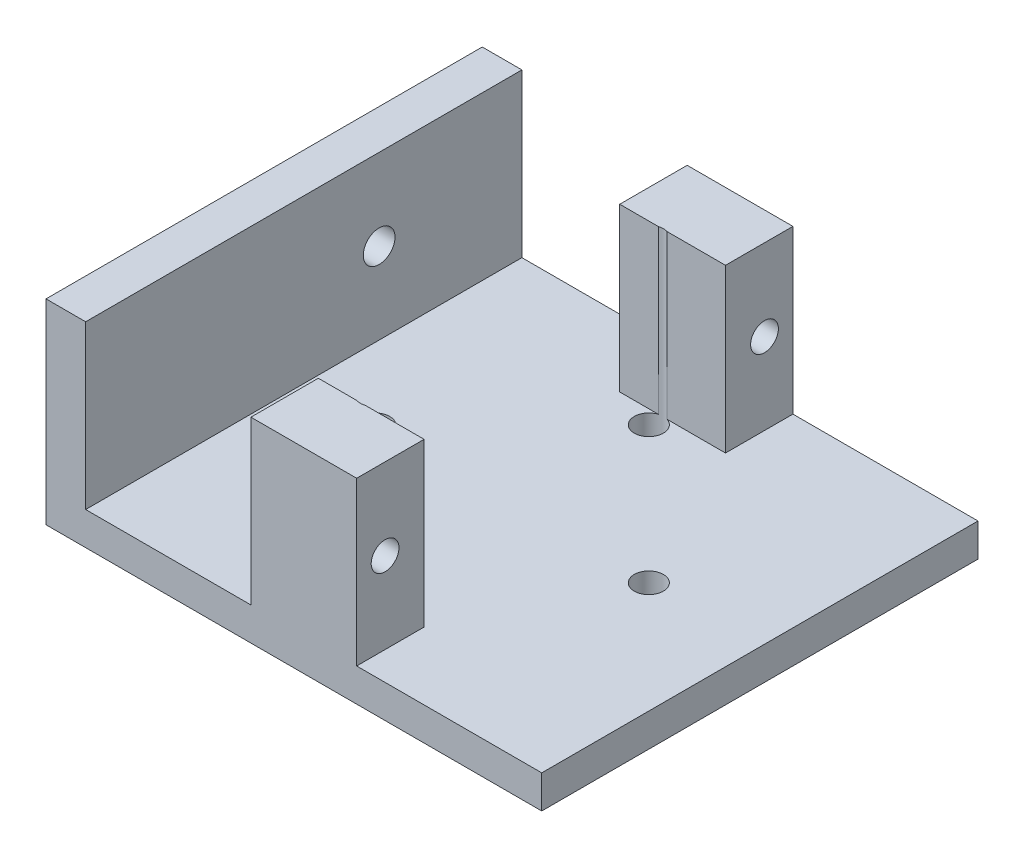
SolidWorks part; units mm, degrees
ref_plane "Ebene vorne" through (0, 0, 0) normal (0, 0, 1) x (1, 0, 0)
ref_plane "Ebene oben" through (0, 0, 0) normal (0, 1, 0) x (1, 0, 0)
ref_plane "Ebene rechts" through (0, 0, 0) normal (1, 0, 0) x (0, 0, -1)
sketch "Skizze1" plane through (0, 0, 0) normal (0, 1, 0) x (1, 0, 0)
  line L1 (-18.75, -16.5) -> (18.75, -16.5)
  line L2 (-18.75, -16.5) -> (-18.75, 16.5)
  line L3 (-18.75, 16.5) -> (18.75, 16.5)
  line L4 (18.75, -16.5) -> (18.75, 16.5)
  line L5 (-18.75, -16.5) -> (18.75, 16.5) construction
  line L6 (-18.75, 16.5) -> (18.75, -16.5) construction
  point P0 (0, 0)
  dimension "D1" = 37.5
  dimension "D2" = 33
extrude "Aufsatz-Linear austragen1" add sketch "Skizze1" along normal blind 2.5
sketch "Skizze2" plane through (0, 2.5, 0) normal (0, 1, 0) x (1, 0, 0)
  line L0 (-18.75, -16.5) -> (18.75, -16.5) construction
  line L1 (-18.75, 16.5) -> (-15.75, 16.5)
  line L2 (-18.75, 16.5) -> (-18.75, -16.5)
  line L3 (-18.75, -16.5) -> (-15.75, -16.5)
  line L4 (-15.75, 16.5) -> (-15.75, -16.5)
  line L5 (18.75, 16.5) -> (-18.75, 16.5) construction
  line L6 (4.75, -16.5) -> (-3.25, -16.5)
  line L7 (4.75, -16.5) -> (4.75, -11.4)
  line L8 (4.75, -11.4) -> (-3.25, -11.4)
  line L9 (-3.25, -16.5) -> (-3.25, -11.4)
  line L10 (4.75, 16.5) -> (-3.25, 16.5)
  line L11 (4.75, 16.5) -> (4.75, 11.4)
  line L12 (4.75, 11.4) -> (-3.25, 11.4)
  line L13 (-3.25, 16.5) -> (-3.25, 11.4)
  dimension "D1" = 3
  dimension "D2" = 20.5
  dimension "D3" = 8
  dimension "D4" = 8
  dimension "D5" = 20.5
  dimension "D6" = 5.1
  dimension "D7" = 5.1
  dimension "D8" = 22.8
extrude "Aufsatz-Linear austragen2" add sketch "Skizze2" along normal blind 12.3
sketch "Skizze3" plane through (0, 14.8, 0) normal (0, 1, 0) x (1, 0, 0)
  line L1 (-15.75, 16.5) -> (-18.75, 16.5)
  line L2 (-15.75, 16.5) -> (-15.75, -16.5)
  line L3 (-15.75, -16.5) -> (-18.75, -16.5)
  line L4 (-18.75, 16.5) -> (-18.75, -16.5)
sketch "Skizze5" plane through (-15.75, 0, 0) normal (1, 0, 0) x (0, 0, -1)
  line L2 (16.5, 14.8) -> (-16.5, 14.8) construction
  line L4 (16.5, 14.8) -> (16.5, 2.5) construction
  circle A1 centre (5.7, 8.65) radius 1.2
  dimension "D2" = 6.15
  dimension "D1" = 2.4
  dimension "D3" = 10.8
sketch "Skizze6" plane through (0, 0, 0) normal (0, -1, 0) x (1, 0, 0)
  arc A0 (1.0984, 10.2915) -> (-1.0984, 10.2915) centre (0, 0) ccw
  circle A1 centre (-10.35, 0) radius 1.1
  circle A2 centre (0, 10.35) radius 1.1
  circle A3 centre (10.35, 0) radius 1.1
  circle A4 centre (0, -10.35) radius 1.1
  arc A5 (10.2915, -1.0984) -> (10.2915, 1.0984) centre (0, 0) ccw
  arc A6 (-1.0984, -10.2915) -> (1.0984, -10.2915) centre (0, 0) ccw
  arc A7 (-10.2915, 1.0984) -> (-10.2915, -1.0984) centre (0, 0) ccw
  dimension "D1" = 20.7
  dimension "D2" = 2.2
  dimension "D3" = 2.2
  dimension "D4" = 2.2
  dimension "D5" = 2.2
extrude "Schnitt-Linear austragen3" cut sketch "Skizze6" against normal through all contours A7 A1 | A1 A7 | A0 A2 | A0 A2 | A3 A5 | A5 A3 | A4 A6 | A6 A4
extrude "Schnitt-Linear austragen4" cut sketch "Skizze5" against normal through all
sketch "Skizze7" plane through (4.75, 0, 0) normal (1, 0, 0) x (0, 0, -1)
  line L0 (16.5, 14.8) -> (16.5, 2.5) construction
  line L1 (16.5, 2.5) -> (16.5, 8.65) construction
  line L2 (16.5, 8.65) -> (-16.5, 8.65) construction
  line L3 (-16.5, 14.8) -> (-16.5, 2.5) construction
  line L4 (13.3, 8.65) -> (13.3, 6.1689) construction
  line L5 (-13.3, 8.65) -> (-13.3, 6.1689) construction
  circle A0 centre (-14.35, 8.65) radius 1.05
  circle A1 centre (14.35, 8.65) radius 1.05
  dimension "D1" = 2.1
  dimension "D2" = 2.1
  dimension "D3" = 3.2
  dimension "D4" = 3.2
extrude "Schnitt-Linear austragen5" cut sketch "Skizze7" against normal blind 10
